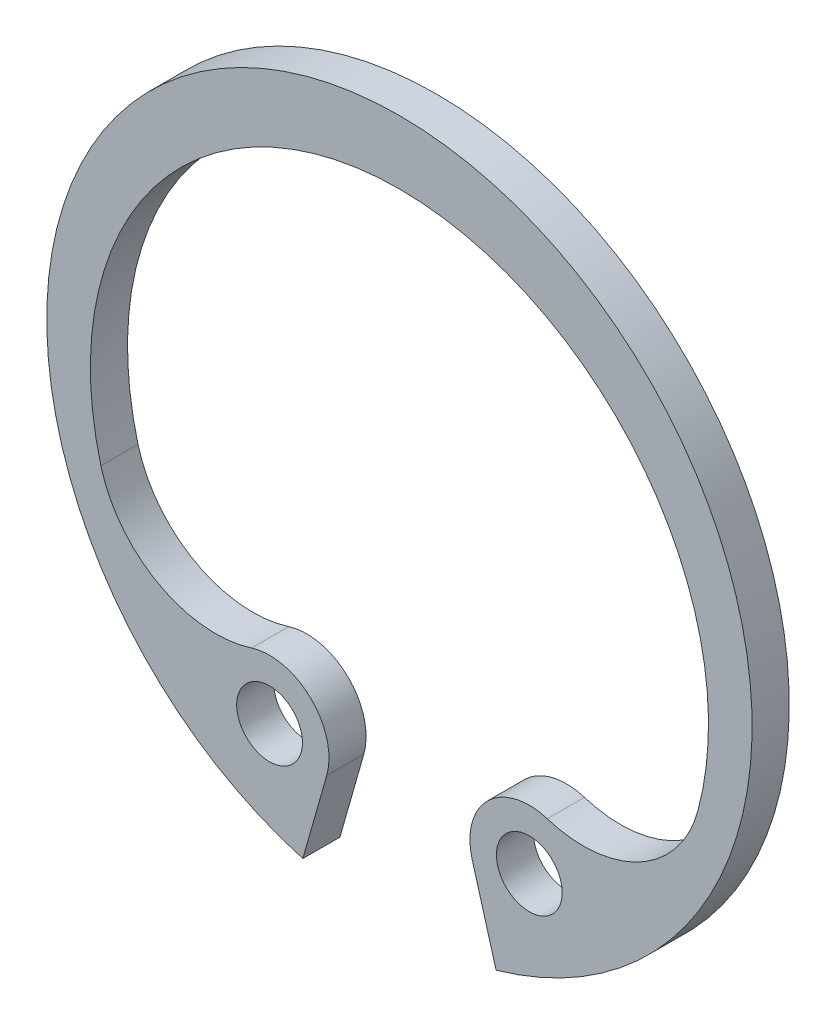
SolidWorks part; units mm, degrees
material "1023 Tôle d'acier au carbone (SS)"
ref_plane "Face" through (0, 0, 0) normal (0, 0, 1) x (1, 0, 0)
ref_plane "Dessus" through (0, 0, 0) normal (0, 1, 0) x (1, 0, 0)
ref_plane "Droite" through (0, 0, 0) normal (1, 0, 0) x (0, 0, -1)
ref_plane "Plan1" through (0, 0, -0.0184) normal (0, 0, 1) x (1, 0, 0)
sketch "Esquisse1" plane through (0, 0, -0.0184) normal (0, 0, 1) x (1, 0, 0)
  line L0 (-2.2182, -7.7722) -> (-1.6699, -5.8476)
  line L1 (1.6699, -5.8476) -> (2.2182, -7.7722)
  circle A0 centre (2.9813, -5.474) radius 0.7548
  circle A1 centre (-2.9813, -5.474) radius 0.7548
  arc A2 (2.2182, -7.7722) -> (-2.2182, -7.7722) centre (0, 0.0138) ccw
  arc A3 (-1.6699, -5.8476) -> (-3.3939, -4.1744) centre (-2.9813, -5.474) ccw
  arc A4 (-3.3939, -4.1744) -> (-6.8534, -2.2804) centre (-4.2191, -1.5753) cw
  arc A5 (-6.8534, -2.2804) -> (6.8534, -2.2804) centre (0, -0.4459) cw
  arc A6 (6.8534, -2.2804) -> (3.3939, -4.1744) centre (4.2191, -1.5753) cw
  arc A7 (3.3939, -4.1744) -> (1.6699, -5.8476) centre (2.9813, -5.474) ccw
extrude "Boss.-Extru.1" add sketch "Esquisse1" against normal blind 0.8522
